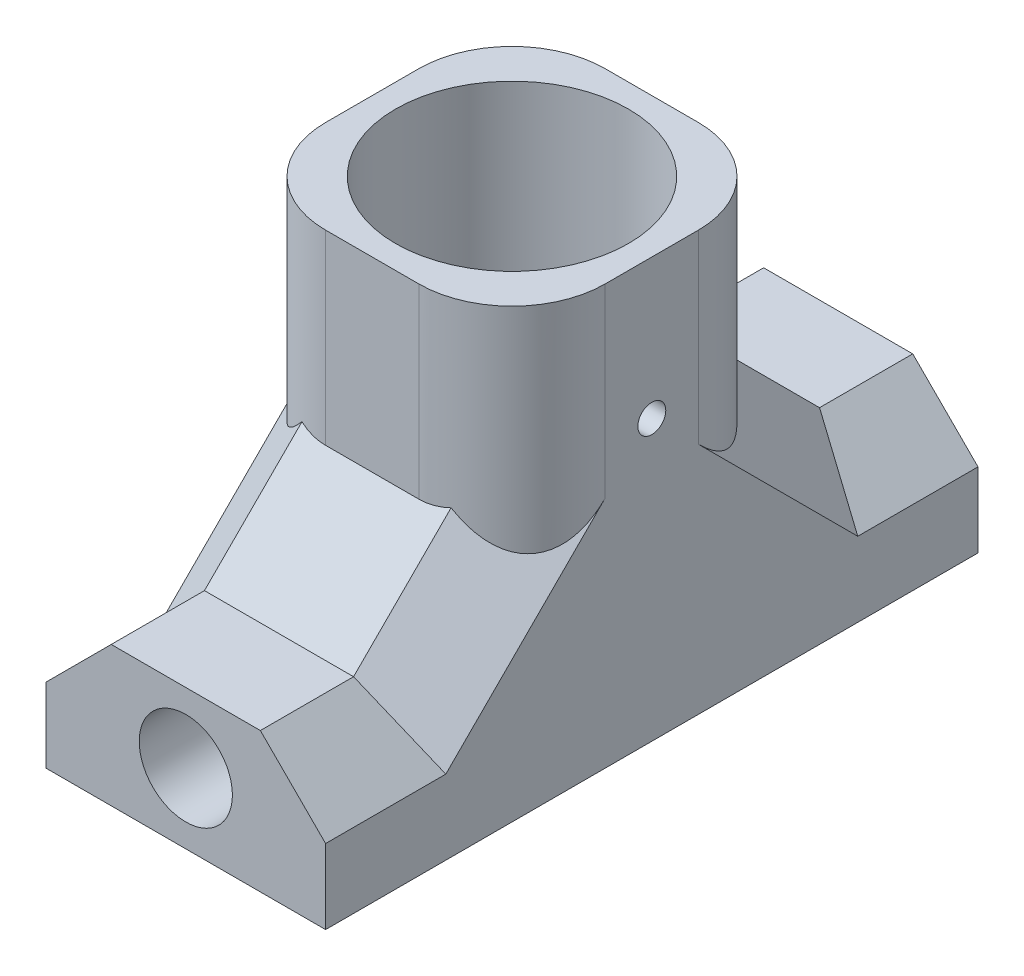
SolidWorks part; units mm, degrees
ref_plane "前基準面" through (0, 0, 0) normal (0, 0, 1) x (1, 0, 0)
ref_plane "上基準面" through (0, 0, 0) normal (0, 1, 0) x (1, 0, 0)
ref_plane "右基準面" through (0, 0, 0) normal (1, 0, 0) x (0, 0, -1)
sketch "草圖1" plane through (0, 0, 0) normal (1, 0, 0) x (0, 0, -1)
  line L0 (50, 15) -> (70, 15)
  line L1 (0, 0) -> (70, 0)
  line L2 (0, 0) -> (0, 15)
  line L3 (0, 15) -> (20, 15)
  line L4 (70, 0) -> (70, 15)
  line L6 (20, 15) -> (20, 45)
  line L7 (20, 45) -> (50, 45)
  line L8 (50, 15) -> (50, 45)
  dimension "D1" = 30
  dimension "D2" = 15
  dimension "D3" = 30
  dimension "D4" = 20
extrude "填料-伸長1" add sketch "草圖1" along normal blind 30
sketch "草圖2" plane through (0, 45, 0) normal (0, 1, 0) x (1, 0, 0)
  line L0 (0, 50) -> (30, 20) construction
  circle A0 centre (15, 35) radius 12.5
  dimension "D1" = 25
extrude "除料-伸長1" cut sketch "草圖2" against normal blind 30
sketch "草圖3" plane through (0, 0, 0) normal (0, 0, 1) x (1, 0, 0)
  line L0 (30, 15) -> (0, 0) construction
  circle A0 centre (15, 7.5) radius 5
  dimension "D1" = 10
extrude "除料-伸長2" cut sketch "草圖3" against normal through all
chamfer "導角1" distance 10 angle 45 2 edges at (15, 15, -50) (15, 15, -20)
fillet "圓角1" radius 10 4 edges at (0, 35, -50) (30, 35, -50) (0, 35, -20) (30, 35, -20)
chamfer "導角2" distance 7 angle 45 8 edges at (0, 15, -5) (0, 25, -20) (0, 15, -65) (0, 25, -50) (30, 15, -65) (30, 25, -50) (30, 15, -5) (30, 25, -20)
sketch "草圖4" plane through (30, 0, 0) normal (1, 0, 0) x (0, 0, -1)
  line L0 (35, 45) -> (35, 30) construction
  line L1 (40, 45) -> (30, 45) construction
  circle A0 centre (35, 30) radius 1.5
  dimension "D2" = 3
  dimension "D1" = 15
extrude "除料-伸長3" cut sketch "草圖4" against normal through all
